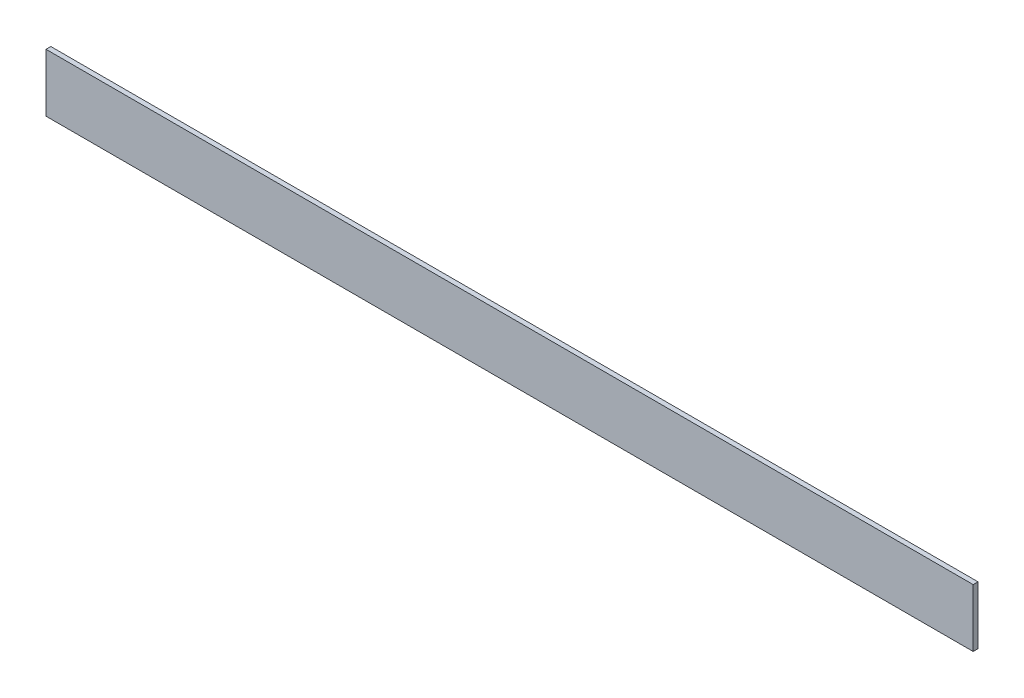
SolidWorks part; units mm, degrees
material "Oak"
ref_plane "Front Plane" through (0, 0, 0) normal (0, 0, 1) x (1, 0, 0)
ref_plane "Top Plane" through (0, 0, 0) normal (0, 1, 0) x (1, 0, 0)
ref_plane "Right Plane" through (0, 0, 0) normal (1, 0, 0) x (0, 0, -1)
sketch "Sketch1" plane through (0, 0, 0) normal (0, 0, 1) x (1, 0, 0)
  line L1 (-480, -30) -> (480, -30)
  line L2 (-480, -30) -> (-480, 30)
  line L3 (-480, 30) -> (480, 30)
  line L4 (480, -30) -> (480, 30)
  line L5 (-480, -30) -> (480, 30) construction
  line L6 (-480, 30) -> (480, -30) construction
  point P0 (0, 0)
  dimension "D1" = 60
  dimension "D2" = 960
extrude "Boss-Extrude1" add sketch "Sketch1" along normal blind 5
